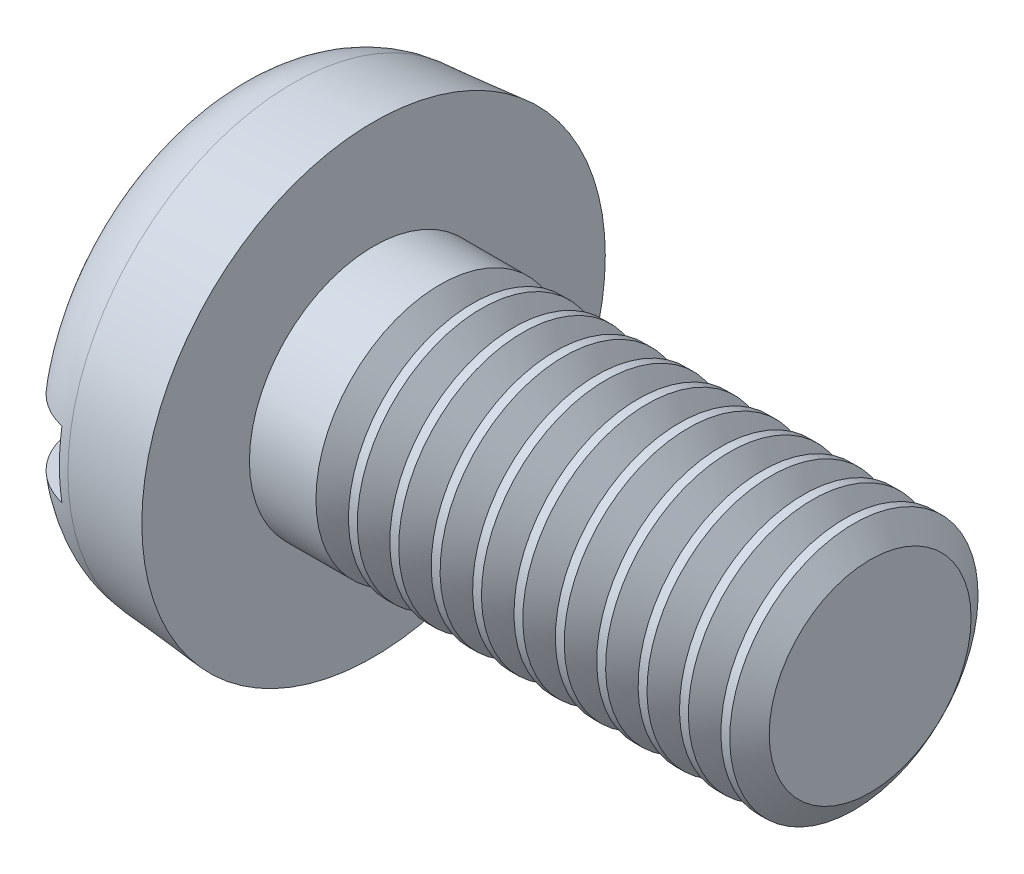
SolidWorks part; units mm, degrees
ref_plane "Plane1" through (0, 0, 0) normal (0, 0, 1) x (1, 0, 0)
ref_plane "Plane2" through (0, 0, 0) normal (0, 1, 0) x (1, 0, 0)
ref_plane "Plane3" through (0, 0, 0) normal (1, 0, 0) x (0, 0, -1)
sketch "BodySke" plane through (0, 0, 0) normal (0, 0, 1) x (1, 0, 0)
  line L0 (1.8, 1.5) -> (1.8, 2.8)
  line L1 (0, 0) -> (0, 2.6425)
  line L2 (-25.4, 0) -> (127, 0) construction
  line L3 (7.8, 0) -> (0, 0)
  line L4 (1.8, 1.5) -> (7.8, 1.5)
  line L5 (7.8, 1.5) -> (7.8, 0)
  line L6 (0, 2.6425) -> (1.8, 2.8)
  line L9 (2.3, 3.0875) -> (2.3, -6.4375) construction
  line L10 (1.8, 6.35) -> (1.8, -3.175) construction
  dimension "Head_ht" = 1.8
  dimension "Diameter" = 3
  dimension "Length" = 6
  dimension "Head_dia" = 5.6
  dimension "Advance" = 0.5
  dimension "Thread_nom" = 6
  dimension "Head_side_angle" = 5
revolve "Base-Revolve" add sketch "BodySke"
cosmetic thread "ThreadCosmetic" [suppressed]
fillet "Fillet1" [suppressed] radius 0.1
fillet "Fillet2" radius 0.9 1 edges at (0, 0, 2.6425)
sketch "Sketch2" plane through (0, 0, 0) normal (1, 0, 0) x (0, 0, -1)
  line L0 (2.8, -0.4) -> (-2.8, -0.4)
  line L1 (2.8, -0.4) -> (2.8, 0.4)
  line L2 (-2.8, 0.4) -> (2.8, 0.4)
  line L3 (-2.8, 0.4) -> (-2.8, -0.4)
  dimension "D1" = 5.6
  dimension "D2" = 2.8
  dimension "Slot_width" = 0.8
  dimension "D3" = 0.4
extrude "Slot" cut sketch "Sketch2" along normal blind 0.7
sketch "ThdSchSke" plane through (0, 0, 0) normal (0, 0, 1) x (1, 0, 0)
  line L0 (2.8, -1.2195) -> (2.6036, -1.5)
  line L1 (2.8, -1.2195) -> (2.9964, -1.5)
  line L2 (2.9964, -1.5) -> (2.9964, -1.875)
  line L3 (-3.175, 0) -> (5.1513, 0) construction
  line L5 (2.9964, -1.875) -> (2.6036, -1.875)
  line L6 (2.6036, -1.875) -> (2.6036, -1.5)
  dimension "Thread_minor" = 2.439
  dimension "Diameter" = 3
  dimension "Start" = 2.8
  dimension "SideAngle" = 55
  dimension "VeeAngle" = 70
  dimension "Overcut" = 3.75
revolve "ThreadSchematic" cut sketch "ThdSchSke" angle 360 about L3
pattern_linear "ThdSchPat" count 11 spacing 0.5 along (1, 0, 0) of "ThreadSchematic"
equation "\"D1@Sketch2\" = \"Head_dia@BodySke\""
equation "\"D2@Sketch2\" = \"D1@Sketch2\" / 2"
equation "\"D3@Sketch2\" = \"Slot_width@Sketch2\" / 2"
equation "\"Thread_length@ThreadCosmetic\" = ((sgn( (\"Length@BodySke\" - \"Advance@BodySke\" * 2.0 ) - \"Thread_nom@BodySke\" )-1)*( (\"Length@BodySke\" - \"Advance@BodySke\"  * 2.0) - \"Thread_nom@BodySke\" ))/-2+ \"Thread_nom@BodySke\""
equation "\"Thread_minor@ThdSchSke\" = \"Thread_minor@ThreadCosmetic\""
equation "\"Diameter@ThdSchSke\" = \"Diameter@BodySke\""
equation "\"Overcut@ThdSchSke\" = \"Diameter@BodySke\" * 1.25"
equation "\"Start@ThdSchSke\" = \"Head_ht@BodySke\" + \"Length@BodySke\" - \"Thread_length@ThreadCosmetic\"  '---Non-countersunk---"
equation "\"Num_threads@ThdSchPat\" = int( \"Thread_length@ThreadCosmetic\" / \"Advance@BodySke\" + 0.999 )  + 1"
equation "\"Advance@ThdSchPat\" = \"Thread_length@ThreadCosmetic\" /  (\"Num_threads@ThdSchPat\" - 1) 'relax it"
